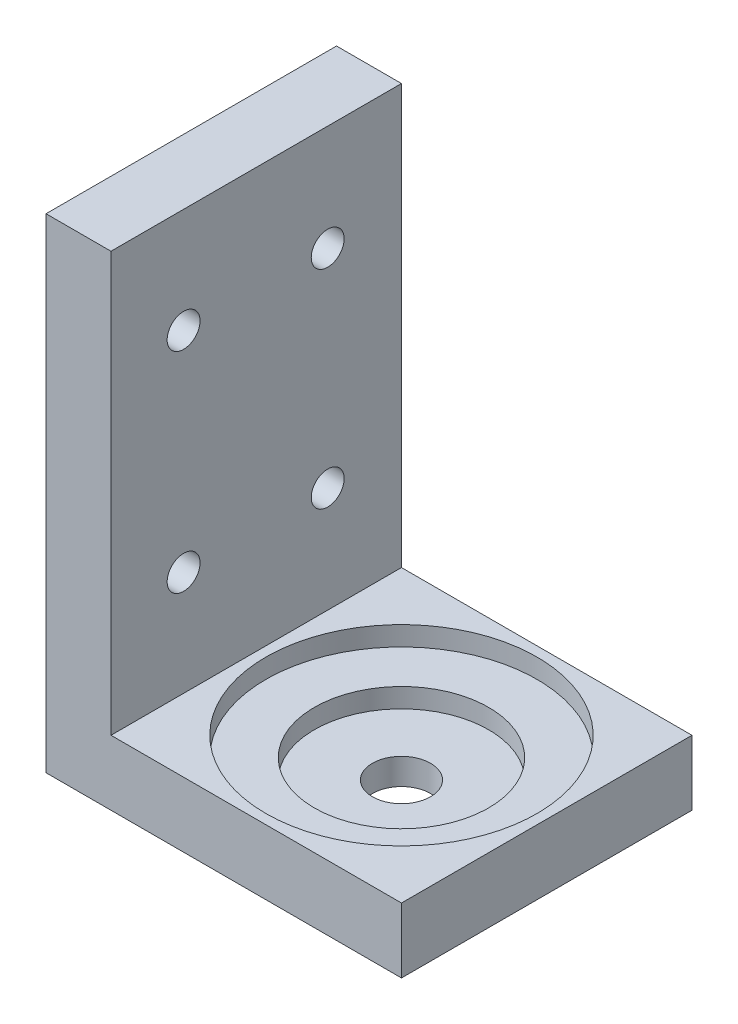
SolidWorks part; units mm, degrees
ref_plane "Front Plane" through (0, 0, 0) normal (0, 0, 1) x (1, 0, 0)
ref_plane "Top Plane" through (0, 0, 0) normal (0, 1, 0) x (1, 0, 0)
ref_plane "Right Plane" through (0, 0, 0) normal (1, 0, 0) x (0, 0, -1)
sketch "Sketch2" plane through (0, 0, 0) normal (0, 1, 0) x (1, 0, 0)
  line L1 (-161.3758, 104.1109) -> (-131.3758, 104.1109)
  line L2 (-161.3758, 104.1109) -> (-161.3758, 74.1109)
  line L3 (-161.3758, 74.1109) -> (-131.3758, 74.1109)
  line L4 (-131.3758, 104.1109) -> (-131.3758, 74.1109)
  dimension "D1" = 30
  dimension "D2" = 30
extrude "Boss-Extrude1" add sketch "Sketch2" along normal blind 6.708
sketch "Sketch5" plane through (0, 6.708, 0) normal (0, 1, 0) x (1, 0, 0)
  line L0 (-161.3758, 89.1109) -> (-131.3758, 89.1109) construction
  line L1 (-161.3758, 104.1109) -> (-161.3758, 74.1109) construction
  line L2 (-131.3758, 74.1109) -> (-131.3758, 104.1109) construction
  circle A0 centre (-146.3758, 89.1109) radius 14
  dimension "D1" = 28
extrude "Cut-Extrude1" cut sketch "Sketch5" against normal blind 2
sketch "Sketch13" plane through (0, 4.708, 0) normal (0, 1, 0) x (1, 0, 0)
  line L0 (-161.3758, 89.1109) -> (-131.3758, 89.1109) construction
  line L1 (-161.3758, 104.1109) -> (-161.3758, 74.1109) construction
  line L2 (-131.3758, 74.1109) -> (-131.3758, 104.1109) construction
  circle A0 centre (-146.3758, 89.1109) radius 9
  dimension "D1" = 18
extrude "Cut-Extrude3" cut sketch "Sketch13" against normal blind 2 contours A0
sketch "Sketch14" plane through (0, 2.708, 0) normal (0, 1, 0) x (1, 0, 0)
  line L0 (-161.3758, 89.1109) -> (-131.3758, 89.1109) construction
  line L1 (-161.3758, 104.1109) -> (-161.3758, 74.1109) construction
  line L2 (-131.3758, 74.1109) -> (-131.3758, 104.1109) construction
  circle A0 centre (-146.3758, 89.1109) radius 9
  dimension "D1" = 18
sketch "Sketch15" plane through (0, 2.708, 0) normal (0, 1, 0) x (1, 0, 0)
  line L0 (-161.3758, 89.1109) -> (-131.3758, 89.1109) construction
  line L1 (-161.3758, 104.1109) -> (-161.3758, 74.1109) construction
  circle A0 centre (-146.3758, 89.1109) radius 3
  dimension "D1" = 6
extrude "Cut-Extrude5" cut sketch "Sketch15" against normal blind 8.35 contours A0
sketch "Sketch16" plane through (0, 0, -74.1109) normal (0, 0, 1) x (1, 0, 0)
  line L1 (-161.3758, 0) -> (-168.0838, 0)
  line L2 (-161.3758, 0) -> (-161.3758, 50)
  line L3 (-161.3758, 50) -> (-168.0838, 50)
  line L4 (-168.0838, 0) -> (-168.0838, 50)
  dimension "D1" = 6.708
  dimension "D2" = 50
extrude "Boss-Extrude3" add sketch "Sketch16" against normal blind 30
sketch "Sketch17" plane through (-161.3758, 0, 0) normal (1, 0, 0) x (0, 0, -1)
  line L0 (89.1109, 50) -> (89.1109, 0) construction
  line L1 (104.1109, 50) -> (74.1109, 50) construction
  line L2 (74.1109, 0) -> (104.1109, 0) construction
  line L3 (74.1109, 28.354) -> (104.1109, 28.354) construction
  line L4 (74.1109, 6.708) -> (74.1109, 50) construction
  line L5 (104.1109, 6.708) -> (104.1109, 50) construction
  line L6 (104.1109, 6.708) -> (74.1109, 6.708) construction
  line L7 (74.1109, 6.708) -> (104.1109, 6.708) construction
  circle A0 centre (81.6109, 17.533) radius 1.7
  circle A1 centre (96.4909, 17.63) radius 1.7
  circle A3 centre (96.4909, 39.078) radius 1.7
  circle A4 centre (81.6109, 39.175) radius 1.7
  dimension "D1" = 3.4
  dimension "D2" = 10.825
  dimension "D3" = 7.5
  dimension "D4" = 3.4
  dimension "D5" = 7.62
  dimension "D6" = 10.922
extrude "Cut-Extrude7" cut sketch "Sketch17" against normal blind 6.708
